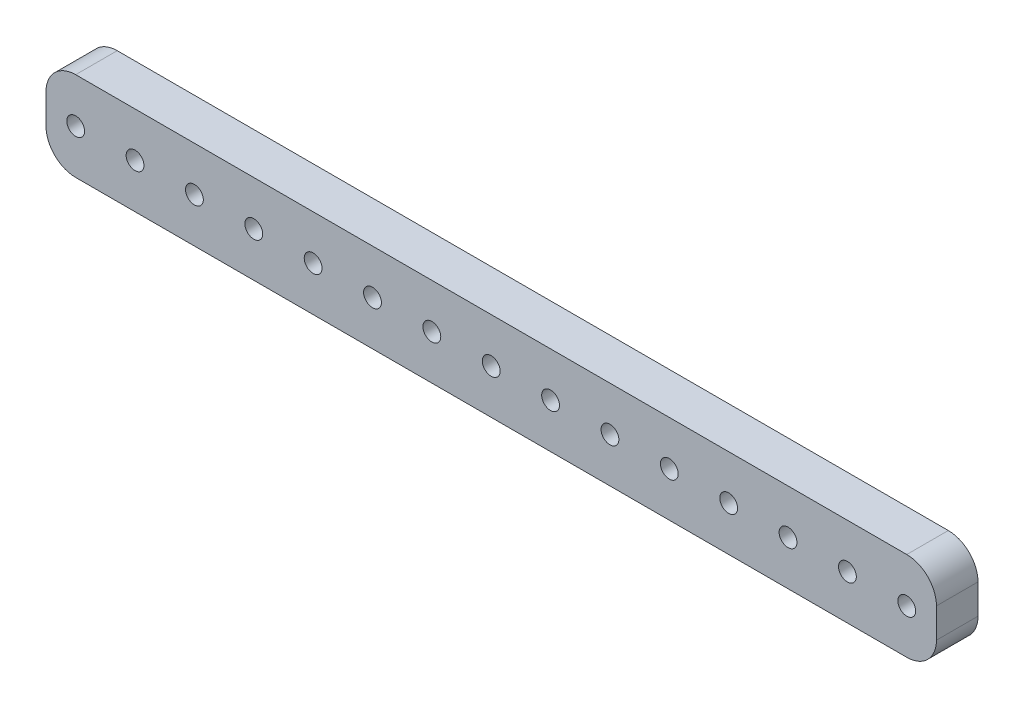
SolidWorks part; units mm, degrees
ref_plane "Front Plane" through (0, 0, 0) normal (0, 0, 1) x (1, 0, 0)
ref_plane "Top Plane" through (0, 0, 0) normal (0, 1, 0) x (1, 0, 0)
ref_plane "Right Plane" through (0, 0, 0) normal (1, 0, 0) x (0, 0, -1)
sketch "Sketch1" plane through (0, 0, 0) normal (0, 0, 1) x (1, 0, 0)
  line L1 (-150, 15) -> (150, 15)
  line L2 (-150, 15) -> (-150, -15)
  line L3 (-150, -15) -> (150, -15)
  line L4 (150, 15) -> (150, -15)
  line L5 (-150, 15) -> (150, -15) construction
  line L6 (-150, -15) -> (150, 15) construction
  point P0 (0, 0)
  dimension "D1" = 300
  dimension "D2" = 30
extrude "Boss-Extrude1" add sketch "Sketch1" along normal blind 14
sketch "Sketch2" plane through (0, 0, 14) normal (0, 0, 1) x (1, 0, 0)
  line L0 (-150, 15) -> (-150, -15) construction
  line L1 (150, -15) -> (150, 15) construction
  circle A0 centre (100, 0) radius 3
  circle A1 centre (-100, 0) radius 3
  circle A2 centre (-140, 0) radius 3
  circle A3 centre (-120, 0) radius 3
  circle A4 centre (120, 0) radius 3
  circle A5 centre (140, 0) radius 3
  circle A6 centre (-80, 0) radius 3
  circle A7 centre (80, 0) radius 3
  circle A8 centre (-60, 0) radius 3
  circle A9 centre (-40, 0) radius 3
  circle A10 centre (60, 0) radius 3
  circle A11 centre (40, 0) radius 3
  circle A12 centre (-20, 0) radius 3
  circle A13 centre (0, 0) radius 3
  circle A14 centre (20, 0) radius 3
  dimension "D1" = 6
  dimension "D2" = 50
  dimension "D3" = 50
  dimension "D4" = 20
  dimension "D5" = 20
  dimension "D6" = 20
  dimension "D7" = 20
  dimension "D8" = 20
  dimension "D9" = 20
  dimension "D10" = 20
  dimension "D11" = 20
  dimension "D12" = 20
  dimension "D13" = 20
  dimension "D14" = 20
  dimension "D15" = 20
  dimension "D16" = 20
extrude "Cut-Extrude1" cut sketch "Sketch2" against normal up to surface (14 mm away) up to face at (0, 0, 0)
fillet "Fillet1" radius 10 4 edges at (-150, -15, 7) (-150, 15, 7) (150, -15, 7) (150, 15, 7)
